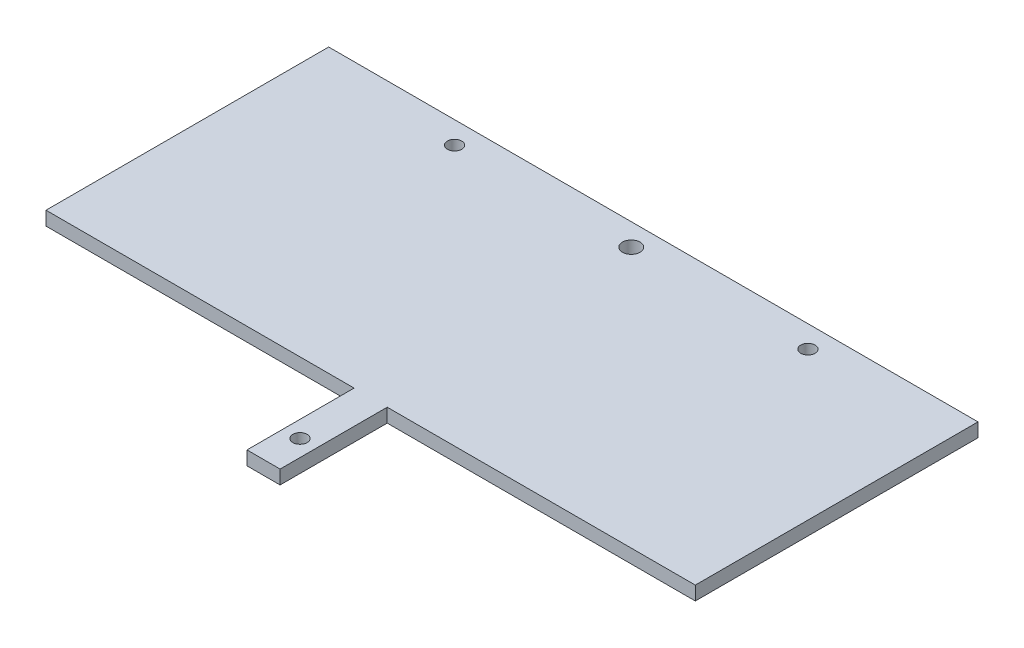
SolidWorks part; units mm, degrees
ref_plane "Front Plane" through (0, 0, 0) normal (0, 0, 1) x (1, 0, 0)
ref_plane "Top Plane" through (0, 0, 0) normal (0, 1, 0) x (1, 0, 0)
ref_plane "Right Plane" through (0, 0, 0) normal (1, 0, 0) x (0, 0, -1)
sketch "Sketch1" plane through (0, 0, 0) normal (0, 1, 0) x (1, 0, 0)
  line L1 (-74.676, 41.402) -> (74.676, 41.402)
  line L2 (-74.676, 41.402) -> (-74.676, -23.622)
  line L3 (-74.676, -23.622) -> (-3.81, -23.622)
  line L4 (74.676, 41.402) -> (74.676, -23.622)
  line L5 (-3.81, -23.622) -> (-3.81, -48.26)
  line L6 (-3.81, -48.26) -> (3.81, -48.26)
  line L7 (3.81, -48.26) -> (3.81, -23.622)
  line L8 (3.81, -23.622) -> (74.676, -23.622)
  point P8 (0, 41.402)
  dimension "D1" = 149.352
  dimension "D2" = 41.402
  dimension "D3" = 7.62
  dimension "D4" = 23.622
  dimension "D5" = 89.662
extrude "Boss-Extrude1" add sketch "Sketch1" against normal blind 3.175
sketch "Sketch2" plane through (0, 0, 0) normal (0, 1, 0) x (1, 0, 0)
  line L0 (-40.64, 36.322) -> (0, 36.322) construction
  line L1 (0, 36.322) -> (40.64, 36.322) construction
  line L3 (-55.4291, 23.622) -> (67.6861, 23.622) construction
  circle A0 centre (-40.64, 36.322) radius 1.651
  circle A1 centre (0, 36.322) radius 2.032
  circle A2 centre (40.64, 36.322) radius 1.651
  circle A3 centre (0, -39.878) radius 1.651
  dimension "D1" = 3.302
  dimension "D4" = 3.302
  dimension "D7" = 3.302
  dimension "D8" = 4.064
  dimension "D2" = 40.64
  dimension "D3" = 12.7
  dimension "D5" = 23.622
  dimension "D6" = 76.2
extrude "Cut-Extrude1" cut sketch "Sketch2" against normal through all
